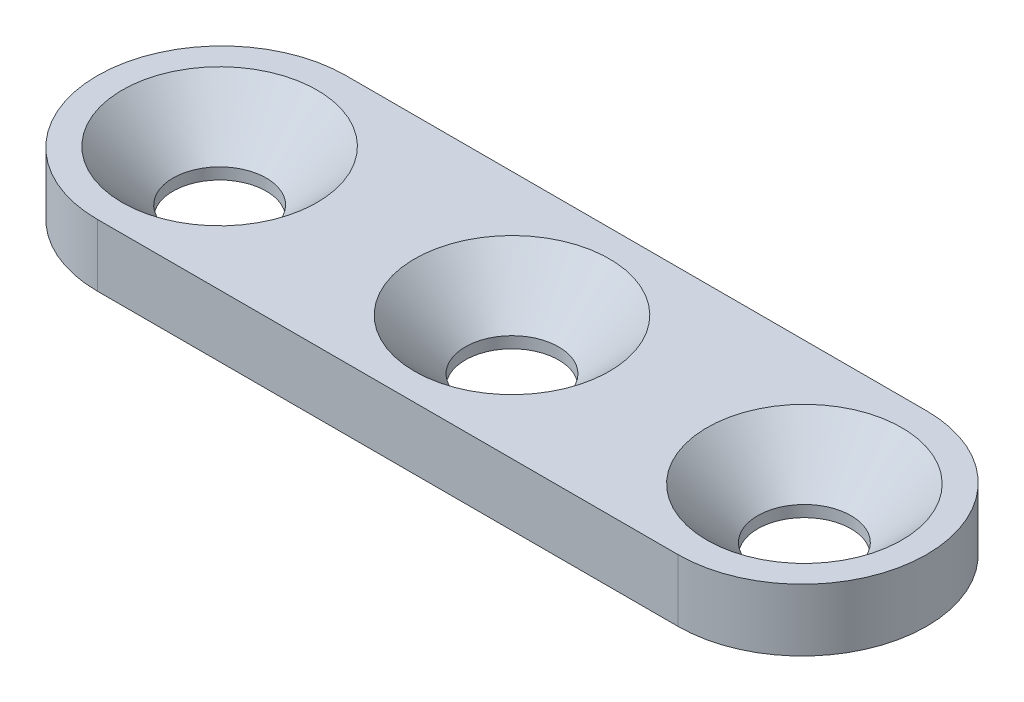
SolidWorks part; units mm, degrees
material "3003 Alloy"
ref_plane "Front Plane" through (0, 0, 0) normal (0, 0, 1) x (1, 0, 0)
ref_plane "Top Plane" through (0, 0, 0) normal (0, 1, 0) x (1, 0, 0)
ref_plane "Right Plane" through (0, 0, 0) normal (1, 0, 0) x (0, 0, -1)
sketch "Sketch2" plane through (0, 0, 0) normal (0, 1, 0) x (1, 0, 0)
  line L0 (14, 0) -> (-14, 0) construction
  line L1 (14, -6) -> (-14, -6)
  line L2 (14, 6) -> (-14, 6)
  arc A0 (14, -6) -> (14, 6) centre (14, 0) ccw
  arc A1 (-14, 6) -> (-14, -6) centre (-14, 0) ccw
  point P2 (0, 0)
  dimension "D1" = 6
  dimension "D2" = 28
extrude "Boss-Extrude1" add sketch "Sketch2" against normal blind 3
hole_wizard "CSK for M4 Flat Head Machine Screw7" positions "Sketch21" profile "Sketch22" countersink size "M4" standard "ANSI Metric" end condition through all
sketch "Sketch21" plane through (0, 0, 0) normal (0, 1, 0) x (1, 0, 0)
  line L0 (-14, -6) -> (14, -6) construction
  point P0 (0, 0)
  point P3 (-14.1, 0)
  point P5 (14.1, 0)
  dimension "D1" = 14.1
  dimension "D2" = 14.1
  dimension "D3" = 6
  dimension "D4" = 6
sketch "Sketch22" plane through (0, 0, 0) normal (1, 0, 0) x (0, 0, 1)
  line L0 (0, 0) -> (0, 3)
  line L1 (0, 3) -> (2.25, 3)
  line L2 (2.25, 3) -> (2.25, 2.45)
  line L3 (2.25, 2.45) -> (4.7, 0)
  line L5 (4.7, 0) -> (0, 0)
  line L6 (-2.25, 2.45) -> (-4.7, 0) construction
  line L11 (0, -6.35) -> (0, 107.95) construction
  dimension "Thru Hole Dia." = 4.5
  dimension "Thru Hole Depth" = 3
  dimension "Near C'Sink Dia." = 9.4
  dimension "Near C'Sink Angle" = 90
